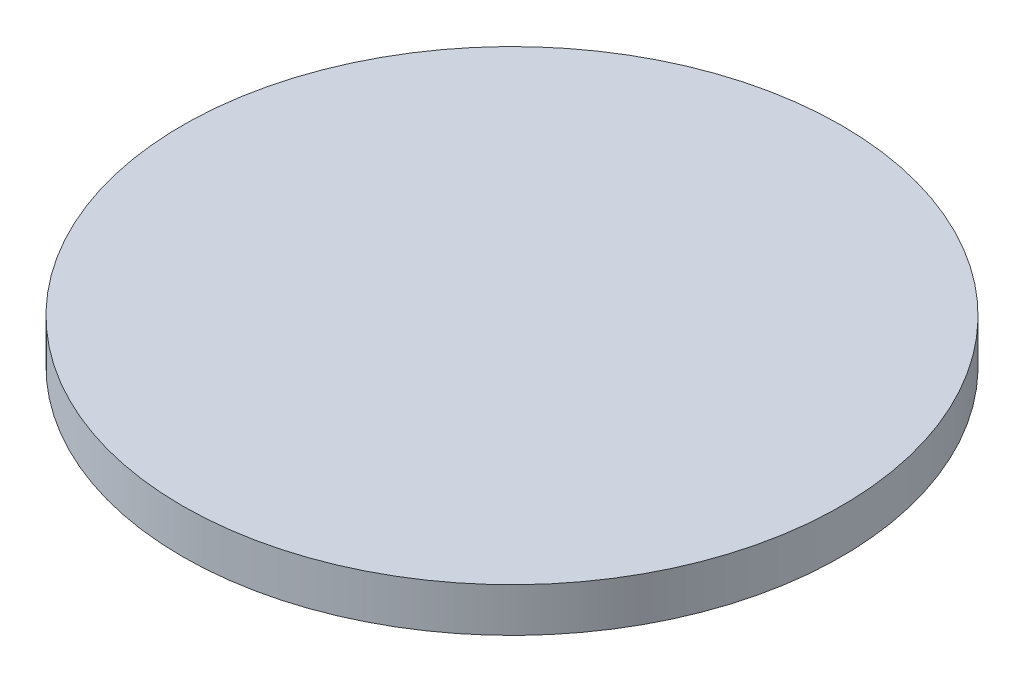
SolidWorks part; units mm, degrees
ref_plane "Alzado" through (0, 0, 0) normal (0, 0, 1) x (1, 0, 0)
ref_plane "Planta" through (0, 0, 0) normal (0, 1, 0) x (1, 0, 0)
ref_plane "Vista lateral" through (0, 0, 0) normal (1, 0, 0) x (0, 0, -1)
sketch "Croquis3" plane through (0, 0, 0) normal (0, 1, 0) x (1, 0, 0)
  circle A0 centre (0, 0) radius 225
  dimension "D1" = 450
extrude "Saliente-Extruir2" add sketch "Croquis3" along normal blind 30
sketch "Croquis5" plane through (0, 0, 0) normal (0, -1, 0) x (1, 0, 0)
  circle A0 centre (0, 0) radius 208.0913
extrude "Cortar-Extruir1" cut sketch "Croquis5" against normal blind 20
